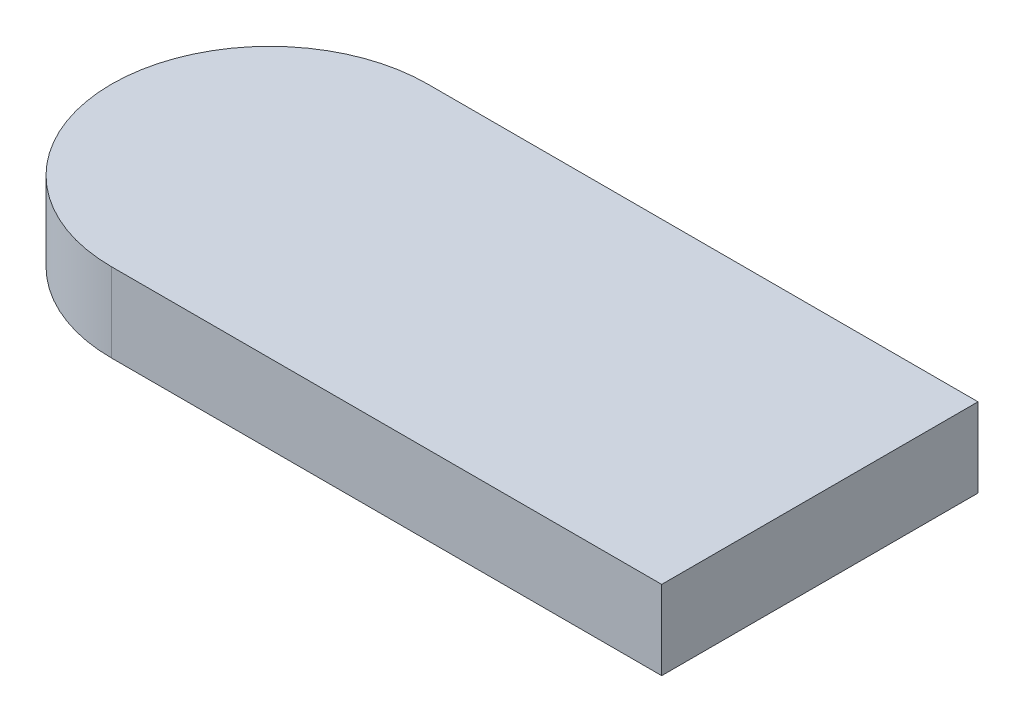
SolidWorks part; units mm, degrees
material "Acrylic (Medium-high impact)"
ref_plane "Front Plane" through (0, 0, 0) normal (0, 0, 1) x (1, 0, 0)
ref_plane "Top Plane" through (0, 0, 0) normal (0, 1, 0) x (1, 0, 0)
ref_plane "Right Plane" through (0, 0, 0) normal (1, 0, 0) x (0, 0, -1)
sketch "스케치1" plane through (0, 0, 0) normal (0, 1, 0) x (1, 0, 0)
  line L1 (-20.77, -11.94) -> (20.77, -11.94)
  line L2 (-20.77, -11.94) -> (-20.77, 11.94) construction
  line L3 (-20.77, 11.94) -> (20.77, 11.94)
  line L4 (20.77, -11.94) -> (20.77, 11.94)
  line L5 (-20.77, -11.94) -> (20.77, 11.94) construction
  line L6 (-20.77, 11.94) -> (20.77, -11.94) construction
  arc A0 (-20.77, 11.94) -> (-20.77, -11.94) centre (-20.77, 0) ccw
  point P0 (0, 0)
  dimension "D1" = 23.88
  dimension "D2" = 41.54
extrude "보스-돌출1" add sketch "스케치1" along normal blind 5.97
